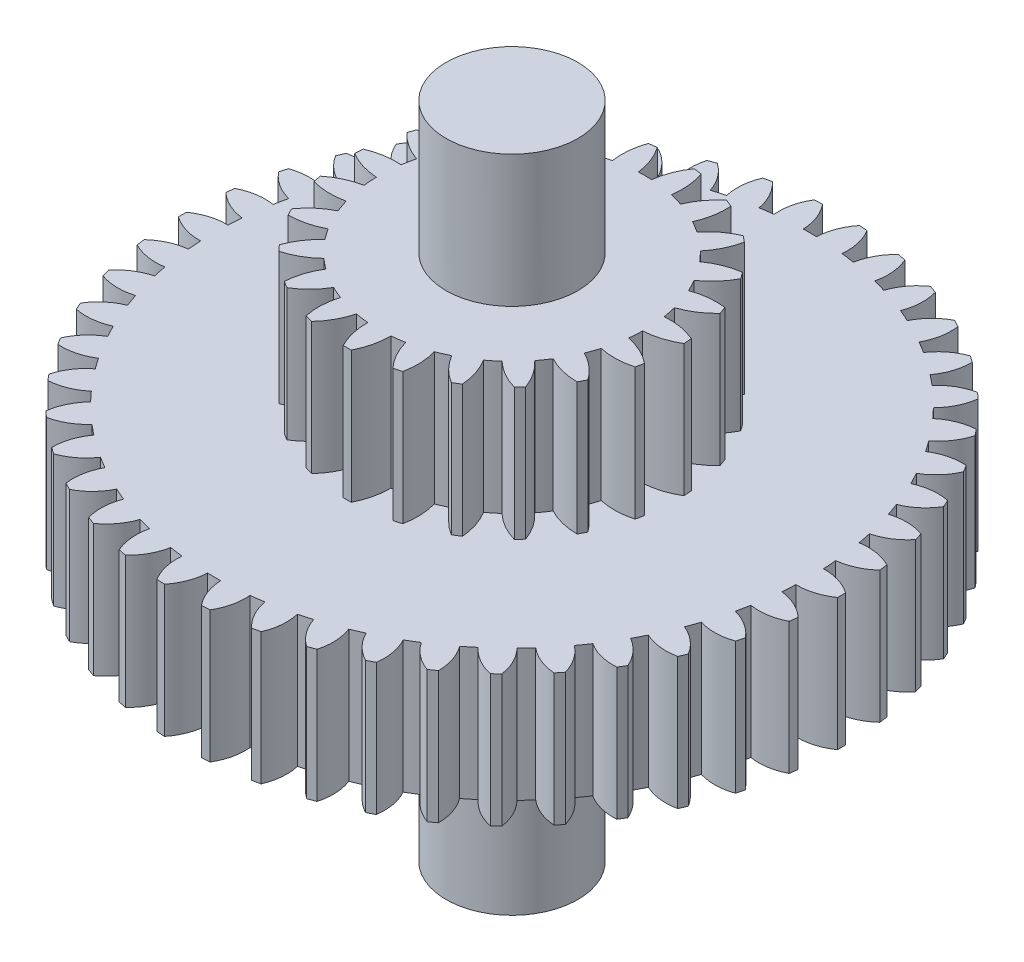
SolidWorks part; units mm, degrees
ref_plane "Front Plane" through (0, 0, 0) normal (0, 0, 1) x (1, 0, 0)
ref_plane "Top Plane" through (0, 0, 0) normal (0, 1, 0) x (1, 0, 0)
ref_plane "Right Plane" through (0, 0, 0) normal (1, 0, 0) x (0, 0, -1)
sketch "Sketch1" plane through (0, 0, 0) normal (0, 1, 0) x (1, 0, 0)
  arc A0 (-1.1228, 2.2337) -> (-1.1773, 2.2054) centre (0, 0) ccw
  arc A1 (-2.1122, 0.8038) -> (-2.1457, 0.7095) centre (0, 0) ccw
  arc A2 (0.05, 2.2594) -> (0.14, 2.4961) centre (0.4546, 2.241) cw
  arc A3 (-0.05, 2.2594) -> (-0.14, 2.4961) centre (-0.4546, 2.241) ccw
  arc A4 (0.3572, 2.2316) -> (0.4786, 2.4538) centre (0.7555, 2.1582) cw
  arc A5 (0.2581, 2.2452) -> (0.2012, 2.4919) centre (-0.1453, 2.282) ccw
  arc A6 (0.6577, 2.1622) -> (0.8082, 2.3657) centre (1.0424, 2.0352) cw
  arc A7 (0.5614, 2.1892) -> (0.5386, 2.4413) centre (0.1668, 2.2805) ccw
  arc A8 (0.946, 2.0525) -> (1.1228, 2.2337) centre (1.3098, 1.8743) cw
  arc A9 (0.8543, 2.0923) -> (0.866, 2.3452) centre (0.4758, 2.2366) ccw
  arc A10 (1.2167, 1.9045) -> (1.4165, 2.06) centre (1.5528, 1.6785) cw
  arc A11 (1.1313, 1.9565) -> (1.1773, 2.2054) centre (0.7759, 2.151) ccw
  arc A12 (1.4647, 1.7211) -> (1.6838, 1.8479) centre (1.7669, 1.4514) cw
  arc A13 (1.3871, 1.7842) -> (1.4666, 2.0246) centre (1.0616, 2.0253) ccw
  arc A14 (1.6854, 1.5057) -> (1.9198, 1.6014) centre (1.9481, 1.1973) cw
  arc A15 (1.6172, 1.5787) -> (1.7287, 1.806) centre (1.3275, 1.8619) ccw
  arc A16 (1.8747, 1.2621) -> (2.12, 1.3251) centre (2.093, 0.9209) cw
  arc A17 (1.8171, 1.3438) -> (1.9585, 1.5538) centre (1.5686, 1.6638) ccw
  arc A18 (2.0291, 0.9951) -> (2.2806, 1.0241) centre (2.1989, 0.6273) cw
  arc A19 (1.9831, 1.0839) -> (2.1518, 1.2727) centre (1.7806, 1.4347) ccw
  arc A20 (2.1457, 0.7095) -> (2.3988, 0.704) centre (2.2638, 0.3221) cw
  arc A21 (2.1122, 0.8038) -> (2.3051, 0.9678) centre (1.9593, 1.1788) ccw
  arc A22 (2.2224, 0.4107) -> (2.4724, 0.3708) centre (2.2866, 0.0108) cw
  arc A23 (2.202, 0.5087) -> (2.4154, 0.6449) centre (2.1016, 0.9011) ccw
  arc A24 (2.2576, 0.1043) -> (2.4998, 0.0307) centre (2.2668, -0.3006) cw
  arc A25 (2.2508, 0.2041) -> (2.4807, 0.31) centre (2.2047, 0.6065) ccw
  arc A26 (2.2508, -0.2041) -> (2.4807, -0.31) centre (2.2047, -0.6065) cw
  arc A27 (2.2576, -0.1043) -> (2.4998, -0.0307) centre (2.2668, 0.3006) ccw
  arc A28 (2.202, -0.5087) -> (2.4154, -0.6449) centre (2.1016, -0.9011) cw
  arc A29 (2.2224, -0.4107) -> (2.4724, -0.3708) centre (2.2866, -0.0108) ccw
  arc A30 (2.1122, -0.8038) -> (2.3051, -0.9678) centre (1.9593, -1.1788) cw
  arc A31 (2.1457, -0.7095) -> (2.3988, -0.704) centre (2.2638, -0.3221) ccw
  arc A32 (1.9831, -1.0839) -> (2.1518, -1.2727) centre (1.7806, -1.4347) cw
  arc A33 (2.0291, -0.9951) -> (2.2806, -1.0241) centre (2.1989, -0.6273) ccw
  arc A34 (1.8171, -1.3438) -> (1.9585, -1.5538) centre (1.5686, -1.6638) cw
  arc A35 (1.8747, -1.2621) -> (2.12, -1.3251) centre (2.093, -0.9209) ccw
  arc A36 (1.6172, -1.5787) -> (1.7287, -1.806) centre (1.3275, -1.8619) cw
  arc A37 (1.6854, -1.5057) -> (1.9198, -1.6014) centre (1.9481, -1.1973) ccw
  arc A38 (1.3871, -1.7842) -> (1.4666, -2.0246) centre (1.0616, -2.0253) cw
  arc A39 (1.4647, -1.7211) -> (1.6838, -1.8479) centre (1.7669, -1.4514) ccw
  arc A40 (1.1313, -1.9565) -> (1.1773, -2.2054) centre (0.7759, -2.151) cw
  arc A41 (1.2167, -1.9045) -> (1.4165, -2.06) centre (1.5528, -1.6785) ccw
  arc A42 (0.8543, -2.0923) -> (0.866, -2.3452) centre (0.4758, -2.2366) cw
  arc A43 (0.946, -2.0525) -> (1.1228, -2.2337) centre (1.3098, -1.8743) ccw
  arc A44 (0.5614, -2.1892) -> (0.5386, -2.4413) centre (0.1668, -2.2805) cw
  arc A45 (0.6577, -2.1622) -> (0.8082, -2.3657) centre (1.0424, -2.0352) ccw
  arc A46 (0.2581, -2.2452) -> (0.2012, -2.4919) centre (-0.1453, -2.282) cw
  arc A47 (0.3572, -2.2316) -> (0.4786, -2.4538) centre (0.7555, -2.1582) ccw
  arc A48 (-0.05, -2.2594) -> (-0.14, -2.4961) centre (-0.4546, -2.241) cw
  arc A49 (0.05, -2.2594) -> (0.14, -2.4961) centre (0.4546, -2.241) ccw
  arc A50 (-0.3572, -2.2316) -> (-0.4786, -2.4538) centre (-0.7555, -2.1582) cw
  arc A51 (-0.2581, -2.2452) -> (-0.2012, -2.4919) centre (0.1453, -2.282) ccw
  arc A52 (-0.6577, -2.1622) -> (-0.8082, -2.3657) centre (-1.0424, -2.0352) cw
  arc A53 (-0.5614, -2.1892) -> (-0.5386, -2.4413) centre (-0.1668, -2.2805) ccw
  arc A54 (-0.946, -2.0525) -> (-1.1228, -2.2337) centre (-1.3098, -1.8743) cw
  arc A55 (-0.8543, -2.0923) -> (-0.866, -2.3452) centre (-0.4758, -2.2366) ccw
  arc A56 (-1.2167, -1.9045) -> (-1.4165, -2.06) centre (-1.5528, -1.6785) cw
  arc A57 (-1.1313, -1.9565) -> (-1.1773, -2.2054) centre (-0.7759, -2.151) ccw
  arc A58 (-1.4647, -1.7211) -> (-1.6838, -1.8479) centre (-1.7669, -1.4514) cw
  arc A59 (-1.3871, -1.7842) -> (-1.4666, -2.0246) centre (-1.0616, -2.0253) ccw
  arc A60 (-1.6854, -1.5057) -> (-1.9198, -1.6014) centre (-1.9481, -1.1973) cw
  arc A61 (-1.6172, -1.5787) -> (-1.7287, -1.806) centre (-1.3275, -1.8619) ccw
  arc A62 (-1.8747, -1.2621) -> (-2.12, -1.3251) centre (-2.093, -0.9209) cw
  arc A63 (-1.8171, -1.3438) -> (-1.9585, -1.5538) centre (-1.5686, -1.6638) ccw
  arc A64 (-2.0291, -0.9951) -> (-2.2806, -1.0241) centre (-2.1989, -0.6273) cw
  arc A65 (-1.9831, -1.0839) -> (-2.1518, -1.2727) centre (-1.7806, -1.4347) ccw
  arc A66 (-2.1457, -0.7095) -> (-2.3988, -0.704) centre (-2.2638, -0.3221) cw
  arc A67 (-2.1122, -0.8038) -> (-2.3051, -0.9678) centre (-1.9593, -1.1788) ccw
  arc A68 (-2.2224, -0.4107) -> (-2.4724, -0.3708) centre (-2.2866, -0.0108) cw
  arc A69 (-2.202, -0.5087) -> (-2.4154, -0.6449) centre (-2.1016, -0.9011) ccw
  arc A70 (-2.2576, -0.1043) -> (-2.4998, -0.0307) centre (-2.2668, 0.3006) cw
  arc A71 (-2.2508, -0.2041) -> (-2.4807, -0.31) centre (-2.2047, -0.6065) ccw
  arc A72 (-2.2508, 0.2041) -> (-2.4807, 0.31) centre (-2.2047, 0.6065) cw
  arc A73 (-2.2576, 0.1043) -> (-2.4998, 0.0307) centre (-2.2668, -0.3006) ccw
  arc A74 (-2.202, 0.5087) -> (-2.4154, 0.6449) centre (-2.1016, 0.9011) cw
  arc A75 (-2.2224, 0.4107) -> (-2.4724, 0.3708) centre (-2.2866, 0.0108) ccw
  arc A76 (-2.1122, 0.8038) -> (-2.3051, 0.9678) centre (-1.9593, 1.1788) cw
  arc A77 (-2.1457, 0.7095) -> (-2.3988, 0.704) centre (-2.2638, 0.3221) ccw
  arc A78 (-1.9831, 1.0839) -> (-2.1518, 1.2727) centre (-1.7806, 1.4347) cw
  arc A79 (-2.0291, 0.9951) -> (-2.2806, 1.0241) centre (-2.1989, 0.6273) ccw
  arc A80 (-1.8171, 1.3438) -> (-1.9585, 1.5538) centre (-1.5686, 1.6638) cw
  arc A81 (-1.8747, 1.2621) -> (-2.12, 1.3251) centre (-2.093, 0.9209) ccw
  arc A82 (-1.6172, 1.5787) -> (-1.7287, 1.806) centre (-1.3275, 1.8619) cw
  arc A83 (-1.6854, 1.5057) -> (-1.9198, 1.6014) centre (-1.9481, 1.1973) ccw
  arc A84 (-1.3871, 1.7842) -> (-1.4666, 2.0246) centre (-1.0616, 2.0253) cw
  arc A85 (-1.4647, 1.7211) -> (-1.6838, 1.8479) centre (-1.7669, 1.4514) ccw
  arc A86 (-1.1313, 1.9565) -> (-1.1773, 2.2054) centre (-0.7759, 2.151) cw
  arc A87 (-1.2167, 1.9045) -> (-1.4165, 2.06) centre (-1.5528, 1.6785) ccw
  arc A88 (-0.8543, 2.0923) -> (-0.866, 2.3452) centre (-0.4758, 2.2366) cw
  arc A89 (-0.946, 2.0525) -> (-1.1228, 2.2337) centre (-1.3098, 1.8743) ccw
  arc A90 (-0.5614, 2.1892) -> (-0.5386, 2.4413) centre (-0.1668, 2.2805) cw
  arc A91 (-0.6577, 2.1622) -> (-0.8082, 2.3657) centre (-1.0424, 2.0352) ccw
  arc A92 (-0.2581, 2.2452) -> (-0.2012, 2.4919) centre (0.1453, 2.282) cw
  arc A93 (-0.3572, 2.2316) -> (-0.4786, 2.4538) centre (-0.7555, 2.1582) ccw
  arc A94 (-1.4165, 2.06) -> (-1.4666, 2.0246) centre (0, 0) ccw
  arc A95 (-1.6838, 1.8479) -> (-1.7287, 1.806) centre (0, 0) ccw
  arc A96 (-1.9198, 1.6014) -> (-1.9585, 1.5538) centre (0, 0) ccw
  arc A97 (-2.12, 1.3251) -> (-2.1518, 1.2727) centre (0, 0) ccw
  arc A98 (-2.2806, 1.0241) -> (-2.3051, 0.9678) centre (0, 0) ccw
  arc A99 (-2.3988, 0.704) -> (-2.4154, 0.6449) centre (0, 0) ccw
  arc A100 (-2.4724, 0.3708) -> (-2.4807, 0.31) centre (0, 0) ccw
  arc A101 (-2.4998, 0.0307) -> (-2.4998, -0.0307) centre (0, 0) ccw
  arc A102 (-2.4807, -0.31) -> (-2.4724, -0.3708) centre (0, 0) ccw
  arc A103 (-2.4154, -0.6449) -> (-2.3988, -0.704) centre (0, 0) ccw
  arc A104 (-2.3051, -0.9678) -> (-2.2806, -1.0241) centre (0, 0) ccw
  arc A105 (-2.1518, -1.2727) -> (-2.12, -1.3251) centre (0, 0) ccw
  arc A106 (-1.9585, -1.5538) -> (-1.9198, -1.6014) centre (0, 0) ccw
  arc A107 (-1.7287, -1.806) -> (-1.6838, -1.8479) centre (0, 0) ccw
  arc A108 (-1.4666, -2.0246) -> (-1.4165, -2.06) centre (0, 0) ccw
  arc A109 (-1.1773, -2.2054) -> (-1.1228, -2.2337) centre (0, 0) ccw
  arc A110 (-0.866, -2.3452) -> (-0.8082, -2.3657) centre (0, 0) ccw
  arc A111 (-0.5386, -2.4413) -> (-0.4786, -2.4538) centre (0, 0) ccw
  arc A112 (-0.2012, -2.4919) -> (-0.14, -2.4961) centre (0, 0) ccw
  arc A113 (0.14, -2.4961) -> (0.2012, -2.4919) centre (0, 0) ccw
  arc A114 (0.4786, -2.4538) -> (0.5386, -2.4413) centre (0, 0) ccw
  arc A115 (0.8082, -2.3657) -> (0.866, -2.3452) centre (0, 0) ccw
  arc A116 (1.1228, -2.2337) -> (1.1773, -2.2054) centre (0, 0) ccw
  arc A117 (1.4165, -2.06) -> (1.4666, -2.0246) centre (0, 0) ccw
  arc A118 (1.6838, -1.8479) -> (1.7287, -1.806) centre (0, 0) ccw
  arc A119 (1.9198, -1.6014) -> (1.9585, -1.5538) centre (0, 0) ccw
  arc A120 (2.12, -1.3251) -> (2.1518, -1.2727) centre (0, 0) ccw
  arc A121 (2.2806, -1.0241) -> (2.3051, -0.9678) centre (0, 0) ccw
  arc A122 (2.3988, -0.704) -> (2.4154, -0.6449) centre (0, 0) ccw
  arc A123 (2.4724, -0.3708) -> (2.4807, -0.31) centre (0, 0) ccw
  arc A124 (2.4998, -0.0307) -> (2.4998, 0.0307) centre (0, 0) ccw
  arc A125 (2.4807, 0.31) -> (2.4724, 0.3708) centre (0, 0) ccw
  arc A126 (2.4154, 0.6449) -> (2.3988, 0.704) centre (0, 0) ccw
  arc A127 (2.3051, 0.9678) -> (2.2806, 1.0241) centre (0, 0) ccw
  arc A128 (2.1518, 1.2727) -> (2.12, 1.3251) centre (0, 0) ccw
  arc A129 (1.9585, 1.5538) -> (1.9198, 1.6014) centre (0, 0) ccw
  arc A130 (1.7287, 1.806) -> (1.6838, 1.8479) centre (0, 0) ccw
  arc A131 (1.4666, 2.0246) -> (1.4165, 2.06) centre (0, 0) ccw
  arc A132 (1.1773, 2.2054) -> (1.1228, 2.2337) centre (0, 0) ccw
  arc A133 (0.866, 2.3452) -> (0.8082, 2.3657) centre (0, 0) ccw
  arc A134 (0.5386, 2.4413) -> (0.4786, 2.4538) centre (0, 0) ccw
  arc A135 (0.2012, 2.4919) -> (0.14, 2.4961) centre (0, 0) ccw
  arc A136 (-0.14, 2.4961) -> (-0.2012, 2.4919) centre (0, 0) ccw
  arc A137 (-0.4786, 2.4538) -> (-0.5386, 2.4413) centre (0, 0) ccw
  arc A138 (-0.8082, 2.3657) -> (-0.866, 2.3452) centre (0, 0) ccw
  arc A139 (-2.202, 0.5087) -> (-2.2224, 0.4107) centre (0, 0) ccw
  arc A140 (-2.2508, 0.2041) -> (-2.2576, 0.1043) centre (0, 0) ccw
  arc A141 (-2.2576, -0.1043) -> (-2.2508, -0.2041) centre (0, 0) ccw
  arc A142 (-2.2224, -0.4107) -> (-2.202, -0.5087) centre (0, 0) ccw
  arc A143 (-2.1457, -0.7095) -> (-2.1122, -0.8038) centre (0, 0) ccw
  arc A144 (-2.0291, -0.9951) -> (-1.9831, -1.0839) centre (0, 0) ccw
  arc A145 (-1.8747, -1.2621) -> (-1.8171, -1.3438) centre (0, 0) ccw
  arc A146 (-1.6854, -1.5057) -> (-1.6172, -1.5787) centre (0, 0) ccw
  arc A147 (-1.4647, -1.7211) -> (-1.3871, -1.7842) centre (0, 0) ccw
  arc A148 (-1.2167, -1.9045) -> (-1.1313, -1.9565) centre (0, 0) ccw
  arc A149 (-0.946, -2.0525) -> (-0.8543, -2.0923) centre (0, 0) ccw
  arc A150 (-0.6577, -2.1622) -> (-0.5614, -2.1892) centre (0, 0) ccw
  arc A151 (-0.3572, -2.2316) -> (-0.2581, -2.2452) centre (0, 0) ccw
  arc A152 (-0.05, -2.2594) -> (0.05, -2.2594) centre (0, 0) ccw
  arc A153 (0.2581, -2.2452) -> (0.3572, -2.2316) centre (0, 0) ccw
  arc A154 (0.5614, -2.1892) -> (0.6577, -2.1622) centre (0, 0) ccw
  arc A155 (0.8543, -2.0923) -> (0.946, -2.0525) centre (0, 0) ccw
  arc A156 (1.1313, -1.9565) -> (1.2167, -1.9045) centre (0, 0) ccw
  arc A157 (1.3871, -1.7842) -> (1.4647, -1.7211) centre (0, 0) ccw
  arc A158 (1.6172, -1.5787) -> (1.6854, -1.5057) centre (0, 0) ccw
  arc A159 (1.8171, -1.3438) -> (1.8747, -1.2621) centre (0, 0) ccw
  arc A160 (1.9831, -1.0839) -> (2.0291, -0.9951) centre (0, 0) ccw
  arc A161 (2.1122, -0.8038) -> (2.1457, -0.7095) centre (0, 0) ccw
  arc A162 (2.202, -0.5087) -> (2.2224, -0.4107) centre (0, 0) ccw
  arc A163 (2.2508, -0.2041) -> (2.2576, -0.1043) centre (0, 0) ccw
  arc A164 (2.2576, 0.1043) -> (2.2508, 0.2041) centre (0, 0) ccw
  arc A165 (2.2224, 0.4107) -> (2.202, 0.5087) centre (0, 0) ccw
  arc A166 (2.1457, 0.7095) -> (2.1122, 0.8038) centre (0, 0) ccw
  arc A167 (2.0291, 0.9951) -> (1.9831, 1.0839) centre (0, 0) ccw
  arc A168 (1.8747, 1.2621) -> (1.8171, 1.3438) centre (0, 0) ccw
  arc A169 (1.6854, 1.5057) -> (1.6172, 1.5787) centre (0, 0) ccw
  arc A170 (1.4647, 1.7211) -> (1.3871, 1.7842) centre (0, 0) ccw
  arc A171 (1.2167, 1.9045) -> (1.1313, 1.9565) centre (0, 0) ccw
  arc A172 (0.946, 2.0525) -> (0.8543, 2.0923) centre (0, 0) ccw
  arc A173 (0.6577, 2.1622) -> (0.5614, 2.1892) centre (0, 0) ccw
  arc A174 (0.3572, 2.2316) -> (0.2581, 2.2452) centre (0, 0) ccw
  arc A175 (0.05, 2.2594) -> (-0.05, 2.2594) centre (0, 0) ccw
  arc A176 (-1.3871, 1.7842) -> (-1.4647, 1.7211) centre (0, 0) ccw
  arc A177 (-1.1313, 1.9565) -> (-1.2167, 1.9045) centre (0, 0) ccw
  arc A178 (-0.8543, 2.0923) -> (-0.946, 2.0525) centre (0, 0) ccw
  arc A179 (-0.5614, 2.1892) -> (-0.6577, 2.1622) centre (0, 0) ccw
  arc A180 (-0.2581, 2.2452) -> (-0.3572, 2.2316) centre (0, 0) ccw
  arc A181 (-1.6172, 1.5787) -> (-1.6854, 1.5057) centre (0, 0) ccw
  arc A182 (-1.8171, 1.3438) -> (-1.8747, 1.2621) centre (0, 0) ccw
  arc A183 (-1.9831, 1.0839) -> (-2.0291, 0.9951) centre (0, 0) ccw
  point P4 (0, 2.26)
  point P5 (0, 2.5)
  point P285 (0, 0)
  dimension "D1" = 5
  dimension "D2" = 0.24
  dimension "D5" = 46
extrude "Boss-Extrude1" add sketch "Sketch1" along normal blind 1
sketch "Sketch2" plane through (0, 0, 0) normal (0, -1, 0) x (1, 0, 0)
  circle A0 centre (0, 0) radius 0.5
  dimension "D1" = 1
extrude "Boss-Extrude2" add sketch "Sketch2" along normal blind 2 and the other way blind 3
sketch "Sketch3" plane through (0, 1, 0) normal (0, 1, 0) x (1, 0, 0)
  arc A0 (-0.765, 0.9886) -> (-0.8122, 0.9501) centre (0, 0) ccw
  arc A1 (-0.4814, 0.8879) -> (-0.5669, 0.8359) centre (0, 0) ccw
  arc A2 (0.05, 1.0088) -> (0.14, 1.2421) centre (0.5621, 0.9453) cw
  arc A3 (-0.05, 1.0088) -> (-0.14, 1.2421) centre (-0.5621, 0.9453) ccw
  arc A4 (0.3203, 0.9579) -> (0.4699, 1.1583) centre (0.7963, 0.7586) cw
  arc A5 (0.224, 0.9848) -> (0.2003, 1.2338) centre (-0.2862, 1.0619) ccw
  arc A6 (0.5669, 0.8359) -> (0.765, 0.9886) centre (0.9714, 0.5157) cw
  arc A7 (0.4814, 0.8879) -> (0.5258, 1.134) centre (0.0109, 1.0997) ccw
  arc A8 (0.7714, 0.652) -> (1.0034, 0.7455) centre (1.0745, 0.2345) cw
  arc A9 (0.7031, 0.7251) -> (0.8122, 0.9501) centre (0.3072, 1.056) ccw
  arc A10 (0.9187, 0.4197) -> (1.1673, 0.4472) centre (1.0979, -0.0641) cw
  arc A11 (0.8727, 0.5085) -> (1.0385, 0.6958) centre (0.5808, 0.934) ccw
  arc A12 (0.9978, 0.1563) -> (1.2446, 0.1156) centre (1.0399, -0.358) cw
  arc A13 (0.9775, 0.2542) -> (1.1877, 0.3898) centre (0.8112, 0.7426) ccw
  arc A14 (1.003, -0.1187) -> (1.2297, -0.2244) centre (0.9048, -0.6253) cw
  arc A15 (1.0098, -0.019) -> (1.2488, 0.0549) centre (0.9815, 0.4962) ccw
  arc A16 (0.9338, -0.3849) -> (1.1235, -0.5479) centre (0.7025, -0.8462) cw
  arc A17 (0.9673, -0.2907) -> (1.2173, -0.284) centre (1.079, 0.213) ccw
  arc A18 (0.7953, -0.6226) -> (0.9341, -0.8307) centre (0.4482, -1.0043) cw
  arc A19 (0.853, -0.5409) -> (1.0955, -0.6019) centre (1.0964, -0.086) ccw
  arc A20 (0.5978, -0.8141) -> (0.6753, -1.0519) centre (0.1606, -1.088) cw
  arc A21 (0.6754, -0.751) -> (0.8925, -0.8752) centre (1.0326, -0.3786) ccw
  arc A22 (0.356, -0.9452) -> (0.3665, -1.1951) centre (-0.1389, -1.091) cw
  arc A23 (0.4478, -0.9053) -> (0.6233, -1.0835) centre (0.8922, -0.6431) ccw
  arc A24 (0.0878, -1.0062) -> (0.0304, -1.2496) centre (-0.4281, -1.0131) cw
  arc A25 (0.1869, -0.9926) -> (0.3078, -1.2115) centre (0.6856, -0.86) ccw
  arc A26 (-0.1869, -0.9926) -> (-0.3078, -1.2115) centre (-0.6856, -0.86) cw
  arc A27 (-0.0878, -1.0062) -> (-0.0304, -1.2496) centre (0.4281, -1.0131) ccw
  arc A28 (-0.4478, -0.9053) -> (-0.6233, -1.0835) centre (-0.8922, -0.6431) cw
  arc A29 (-0.356, -0.9452) -> (-0.3665, -1.1951) centre (0.1389, -1.091) ccw
  arc A30 (-0.6754, -0.751) -> (-0.8925, -0.8752) centre (-1.0326, -0.3786) cw
  arc A31 (-0.5978, -0.8141) -> (-0.6753, -1.0519) centre (-0.1606, -1.088) ccw
  arc A32 (-0.853, -0.5409) -> (-1.0955, -0.6019) centre (-1.0964, -0.086) cw
  arc A33 (-0.7953, -0.6226) -> (-0.9341, -0.8307) centre (-0.4482, -1.0043) ccw
  arc A34 (-0.9673, -0.2907) -> (-1.2173, -0.284) centre (-1.079, 0.213) cw
  arc A35 (-0.9338, -0.3849) -> (-1.1235, -0.5479) centre (-0.7025, -0.8462) ccw
  arc A36 (-1.0098, -0.019) -> (-1.2488, 0.0549) centre (-0.9815, 0.4962) cw
  arc A37 (-1.003, -0.1187) -> (-1.2297, -0.2244) centre (-0.9048, -0.6253) ccw
  arc A38 (-0.9775, 0.2542) -> (-1.1877, 0.3898) centre (-0.8112, 0.7426) cw
  arc A39 (-0.9978, 0.1563) -> (-1.2446, 0.1156) centre (-1.0399, -0.358) ccw
  arc A40 (-0.8727, 0.5085) -> (-1.0385, 0.6958) centre (-0.5808, 0.934) cw
  arc A41 (-0.9187, 0.4197) -> (-1.1673, 0.4472) centre (-1.0979, -0.0641) ccw
  arc A42 (-0.7031, 0.7251) -> (-0.8122, 0.9501) centre (-0.3072, 1.056) cw
  arc A43 (-0.7714, 0.652) -> (-1.0034, 0.7455) centre (-1.0745, 0.2345) ccw
  arc A44 (-0.4814, 0.8879) -> (-0.5258, 1.134) centre (-0.0109, 1.0997) cw
  arc A45 (-0.5669, 0.8359) -> (-0.765, 0.9886) centre (-0.9714, 0.5157) ccw
  arc A46 (-0.224, 0.9848) -> (-0.2003, 1.2338) centre (0.2862, 1.0619) cw
  arc A47 (-0.3203, 0.9579) -> (-0.4699, 1.1583) centre (-0.7963, 0.7586) ccw
  arc A48 (-1.0034, 0.7455) -> (-1.0385, 0.6958) centre (0, 0) ccw
  arc A49 (-1.2446, 0.1156) -> (-1.2488, 0.0549) centre (0, 0) ccw
  arc A50 (-1.1673, 0.4472) -> (-1.1877, 0.3898) centre (0, 0) ccw
  arc A51 (-1.2297, -0.2244) -> (-1.2173, -0.284) centre (0, 0) ccw
  arc A52 (-1.1235, -0.5479) -> (-1.0955, -0.6019) centre (0, 0) ccw
  arc A53 (-0.9341, -0.8307) -> (-0.8925, -0.8752) centre (0, 0) ccw
  arc A54 (-0.3665, -1.1951) -> (-0.3078, -1.2115) centre (0, 0) ccw
  arc A55 (-0.6753, -1.0519) -> (-0.6233, -1.0835) centre (0, 0) ccw
  arc A56 (-0.0304, -1.2496) -> (0.0304, -1.2496) centre (0, 0) ccw
  arc A57 (0.6233, -1.0835) -> (0.6753, -1.0519) centre (0, 0) ccw
  arc A58 (0.8925, -0.8752) -> (0.9341, -0.8307) centre (0, 0) ccw
  arc A59 (0.3078, -1.2115) -> (0.3665, -1.1951) centre (0, 0) ccw
  arc A60 (1.2173, -0.284) -> (1.2297, -0.2244) centre (0, 0) ccw
  arc A61 (1.0955, -0.6019) -> (1.1235, -0.5479) centre (0, 0) ccw
  arc A62 (1.2488, 0.0549) -> (1.2446, 0.1156) centre (0, 0) ccw
  arc A63 (1.1877, 0.3898) -> (1.1673, 0.4472) centre (0, 0) ccw
  arc A64 (1.0385, 0.6958) -> (1.0034, 0.7455) centre (0, 0) ccw
  arc A65 (0.8122, 0.9501) -> (0.765, 0.9886) centre (0, 0) ccw
  arc A66 (0.5258, 1.134) -> (0.4699, 1.1583) centre (0, 0) ccw
  arc A67 (0.2003, 1.2338) -> (0.14, 1.2421) centre (0, 0) ccw
  arc A68 (-0.4699, 1.1583) -> (-0.5258, 1.134) centre (0, 0) ccw
  arc A69 (-0.14, 1.2421) -> (-0.2003, 1.2338) centre (0, 0) ccw
  arc A70 (-0.7031, 0.7251) -> (-0.7714, 0.652) centre (0, 0) ccw
  arc A71 (-0.9775, 0.2542) -> (-0.9978, 0.1563) centre (0, 0) ccw
  arc A72 (-1.0098, -0.019) -> (-1.003, -0.1187) centre (0, 0) ccw
  arc A73 (-0.9673, -0.2907) -> (-0.9338, -0.3849) centre (0, 0) ccw
  arc A74 (-0.853, -0.5409) -> (-0.7953, -0.6226) centre (0, 0) ccw
  arc A75 (-0.224, 0.9848) -> (-0.3203, 0.9579) centre (0, 0) ccw
  arc A76 (0.05, 1.0088) -> (-0.05, 1.0088) centre (0, 0) ccw
  arc A77 (0.3203, 0.9579) -> (0.224, 0.9848) centre (0, 0) ccw
  arc A78 (0.5669, 0.8359) -> (0.4814, 0.8879) centre (0, 0) ccw
  arc A79 (0.7714, 0.652) -> (0.7031, 0.7251) centre (0, 0) ccw
  arc A80 (0.9187, 0.4197) -> (0.8727, 0.5085) centre (0, 0) ccw
  arc A81 (0.9978, 0.1563) -> (0.9775, 0.2542) centre (0, 0) ccw
  arc A82 (1.003, -0.1187) -> (1.0098, -0.019) centre (0, 0) ccw
  arc A83 (0.9338, -0.3849) -> (0.9673, -0.2907) centre (0, 0) ccw
  arc A84 (0.7953, -0.6226) -> (0.853, -0.5409) centre (0, 0) ccw
  arc A85 (0.5978, -0.8141) -> (0.6754, -0.751) centre (0, 0) ccw
  arc A86 (0.356, -0.9452) -> (0.4478, -0.9053) centre (0, 0) ccw
  arc A87 (0.0878, -1.0062) -> (0.1869, -0.9926) centre (0, 0) ccw
  arc A88 (-0.1869, -0.9926) -> (-0.0878, -1.0062) centre (0, 0) ccw
  arc A89 (-0.4478, -0.9053) -> (-0.356, -0.9452) centre (0, 0) ccw
  arc A90 (-0.6754, -0.751) -> (-0.5978, -0.8141) centre (0, 0) ccw
  arc A91 (-0.8727, 0.5085) -> (-0.9187, 0.4197) centre (0, 0) ccw
  point P4 (0, 1.25)
  point P5 (0, 1.01)
  point P147 (0, 0)
  dimension "D1" = 2.5
  dimension "D2" = 0.24
  dimension "D5" = 23
extrude "Boss-Extrude3" add sketch "Sketch3" along normal blind 1 contours A30 A90 A31 A55 A28 A89 A29 A54 A26 A88 A27 A56 A24 A87 A25 A59 A22 A86 A23 A57 A20 A85 A21 A58 A18 A84 A19 A61 A16 A83 A17 A60 A14 A82 A15 A62 A12 A81 A13 A63 A10 A80 A11 A64 A8 A79 A9 A65 A6 A78 A7
